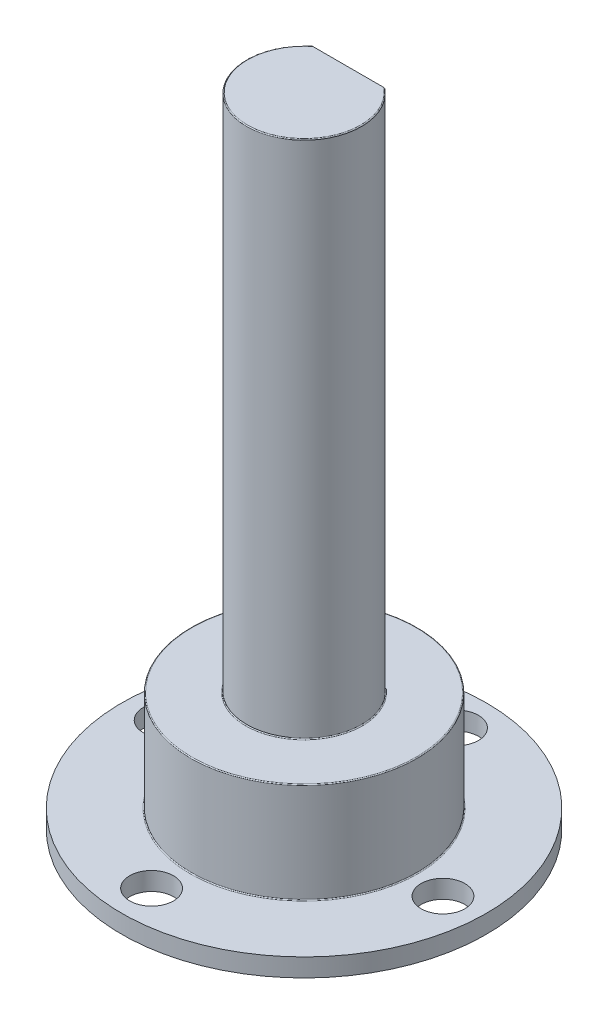
SolidWorks part; units mm, degrees
material "ABS"
ref_plane "Plan de face" through (0, 0, 0) normal (0, 0, 1) x (1, 0, 0)
ref_plane "Plan de dessus" through (0, 0, 0) normal (0, 1, 0) x (1, 0, 0)
ref_plane "Plan de droite" through (0, 0, 0) normal (1, 0, 0) x (0, 0, -1)
sketch "Esquisse2" plane through (0, 0, 0) normal (0, 0, 1) x (1, 0, 0)
  line L0 (0, 35) -> (3.15, 35)
  line L3 (6.2, 3) -> (6.2, 1)
  line L4 (6.2, 1) -> (10, 1)
  line L5 (10, 1) -> (10, 0)
  line L6 (10, 0) -> (4.5, 0)
  line L7 (4.5, 0) -> (4.5, 3)
  line L8 (4.5, 3) -> (0, 3)
  line L9 (0, 3) -> (0, 35)
  line L11 (3.15, 35) -> (3.15, 6.5)
  line L12 (3.15, 6.5) -> (6.2, 6.5)
  line L13 (6.2, 3) -> (6.2, 6.5)
  point P2 (1.575, 35)
  dimension "D1" = 10
  dimension "D2" = 35
  dimension "D3" = 0
  dimension "D4" = 1
  dimension "D5" = 4.5
  dimension "D6" = 2
  dimension "D7" = 6.5
  dimension "D8" = 3
  dimension "D9" = 3.15
  dimension "D10" = 0
  dimension "D12" = 1.7
revolve "Révolution2" add sketch "Esquisse2" angle 360 about L9
sketch "Esquisse3" plane through (0, 35, 0) normal (0, 1, 0) x (1, 0, 0)
  line L1 (-3.6413, 2.4219) -> (2.9365, 2.4219)
  line L2 (-3.6413, 2.4219) -> (-3.6413, 3.808)
  line L3 (-3.6413, 3.808) -> (2.9365, 3.808)
  line L4 (2.9365, 2.4219) -> (2.9365, 3.808)
  dimension "D1" = 6.5779
extrude "Enlèv. mat.-Extru.1" cut sketch "Esquisse3" against normal up to surface (28.5 mm away) contours L4 L3 L2 L1 up to face at (0, 6.5, -3.15)
hole_wizard "Dégagement M21" positions "Esquisse4" profile "Esquisse5" hole size "M2" standard "Ansi Metric" end condition up to next
sketch "Esquisse4" plane through (0, 1, 0) normal (0, 1, 0) x (1, 0, 0)
  circle A0 centre (0, 0) radius 8 construction
  point P0 (0.3713, 7.9914)
  dimension "D1" = 16
sketch "Esquisse5" plane through (0.3713, 1, -7.9914) normal (1, 0, 0) x (0, 0, 1)
  line L0 (0, 0) -> (0, 1.001)
  line L1 (0, 1.001) -> (1.2, 1.001)
  line L2 (1.2, 1.001) -> (1.2, 0)
  line L5 (1.2, 0) -> (0, 0)
  line L11 (0, -6.35) -> (0, 107.95) construction
  dimension "Diamètre du perçage jusqu'au prochain" = 2.4
  dimension "Profondeur du perçage jusqu'au prochain" = 1.001
pattern_circular "Répétition circulaire1" count 4 over 360 about axis through (0, 0, 0) along (0, 1, 0) of "Dégagement M21"
fillet "Congé1" radius 0.05 4 edges at (0, 6.5, 3.15) (0, 6.5, -6.2) (0, 1, -6.2) (0, 35, 3.15)
